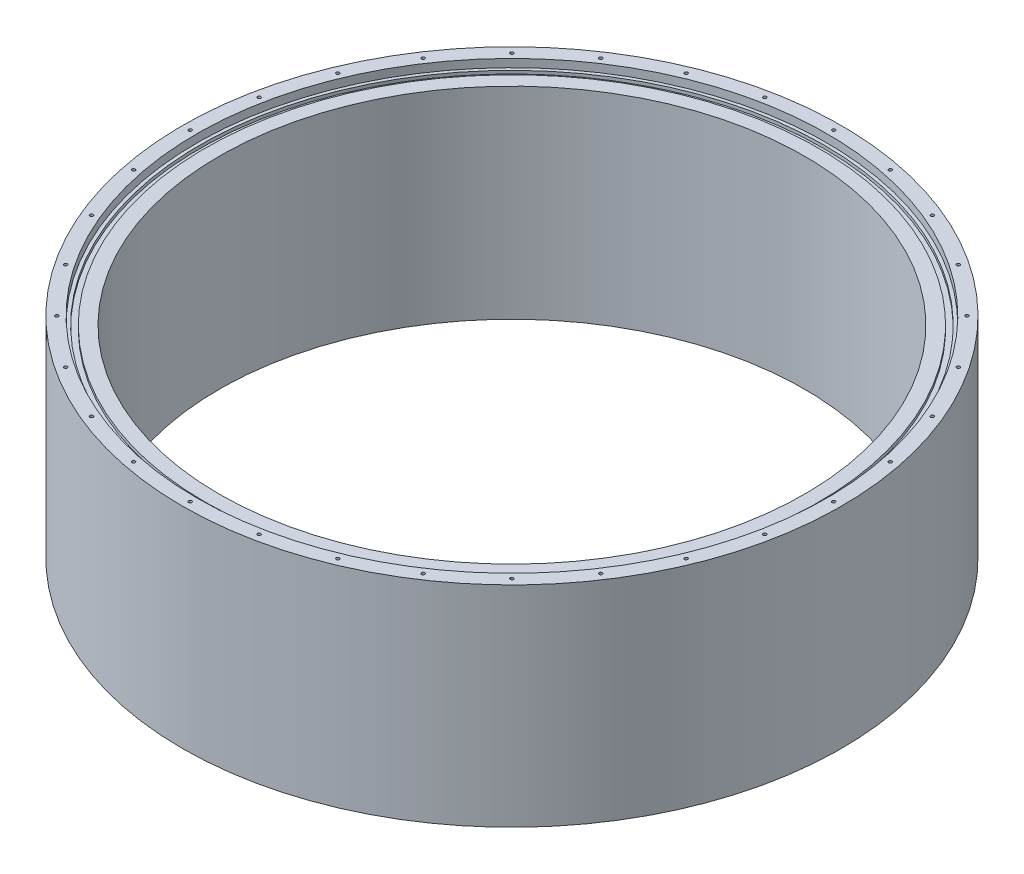
SolidWorks part; units mm, degrees
material "PVC Rigid"
ref_plane "Front" through (0, 0, 0) normal (0, 0, 1) x (1, 0, 0)
ref_plane "Top" through (0, 0, 0) normal (0, 1, 0) x (1, 0, 0)
ref_plane "Right" through (0, 0, 0) normal (1, 0, 0) x (0, 0, -1)
sketch "Sketch1" plane through (0, 0, 0) normal (0, 0, 1) x (1, 0, 0)
  line L0 (225.6, 74.685) -> (243, 74.685)
  line L1 (243, 74.685) -> (243, 80.885)
  line L2 (243, 80.885) -> (254, 80.885)
  line L3 (254, 80.885) -> (254, -80.885)
  line L4 (254, -80.885) -> (225.6, -80.885)
  line L5 (225.6, -80.885) -> (225.6, 74.685)
  line L6 (0, 80.885) -> (0, -80.885) construction
  line L7 (0, 0) -> (225.6, 0) construction
  dimension "D1" = 508
  dimension "D2" = 11
  dimension "D3" = 28.4
  dimension "D4" = 6.2
  dimension "D5" = 161.77
  dimension "D6" = 225.6
  dimension "D7" = 155.57
revolve "Revolve1" add sketch "Sketch1" angle 360 about L6
sketch "Sketch2" plane through (0, 0, 0) normal (0, 0, 1) x (1, 0, 0)
  line L0 (0, 80.885) -> (0, -80.885) construction
  line L1 (254, 80.885) -> (-254, 80.885) construction
  line L2 (-254, -80.885) -> (254, -80.885) construction
  line L3 (240.5, 72.272) -> (240.5, -77.587) construction
  line L4 (236.3344, 74.685) -> (240.5, 74.685)
  line L5 (236.3344, 74.685) -> (236.3344, 72.272)
  line L6 (236.3344, 72.272) -> (240.5, 72.272)
  line L7 (240.5, 74.685) -> (240.5, 72.272)
  line L8 (225.6, 74.685) -> (-225.6, 74.685) construction
  line L9 (225.6, 74.685) -> (-225.6, 74.685) construction
  line L10 (254, -80.885) -> (254, 80.885) construction
  line L12 (236.3344, -78.472) -> (240.5, -78.472) construction
  line L13 (236.3344, -78.472) -> (236.3344, -80.885) construction
  line L14 (236.3344, -80.885) -> (240.5, -80.885) construction
  line L15 (240.5, -78.472) -> (240.5, -80.885) construction
  dimension "D1" = 13.5
  dimension "D2" = 2.413
  dimension "D3" = 4.1656
revolve "Cut-Revolve1" cut sketch "Sketch2" angle 360 about L0
hole_wizard "M3x0.5 Tapped Hole1" positions "Sketch3" profile "Sketch4" tap size "M3x0.5" standard "ANSI Metric"
sketch "Sketch3" plane through (0, 80.885, 0) normal (0, 1, 0) x (1, 0, 0)
  point P0 (248, 0)
  dimension "D1" = 248
sketch "Sketch4" plane through (248, 80.885, 0) normal (1, 0, 0) x (0, 0, 1)
  line L0 (0, 0) -> (0, 10.2511)
  line L1 (0, 10.2511) -> (1.25, 9.5)
  line L2 (1.25, 9.5) -> (1.25, 0)
  line L5 (1.25, 0) -> (0, 0)
  line L10 (0, 10.2511) -> (-1.25, 9.5) construction
  line L11 (0, -6.35) -> (0, 107.95) construction
  dimension "Tap Drill Dia." = 2.5
  dimension "Tap Drill Depth" = 9.5
  dimension "Drill Angle" = 118
cosmetic thread "Hole Thread1" parameters "D1"=8, "D2"=3
pattern_circular "CirPattern1" count 32 over 360 about axis through (0, 0, 0) along (0, 1, 0) of "M3x0.5 Tapped Hole1"
mirror "Mirror1" about plane through (0, 0, 0) normal (0, 1, 0) of "CirPattern1", "M3x0.5 Tapped Hole1"
hole_wizard "Ø5.0mm Dowel Hole1" positions "Sketch5" profile "Sketch6" hole size "Ø5.0" standard "ANSI Metric"
sketch "Sketch5" plane through (0, -80.885, 0) normal (0, -1, 0) x (-1, 0, 0)
  line L2 (0, 0) -> (0, 204.5498) construction
  line L3 (-23.6739, 245.8629) -> (0, 0) construction
  line L4 (0, 0) -> (24.3723, -253.116) construction
  circle A1 centre (0, 0) radius 247
  point P6 (-23.6739, 245.8629)
  point P8 (23.6739, -245.8629)
  dimension "D2" = 494
  dimension "D1" = 5.5
sketch "Sketch6" plane through (-23.6739, -80.885, 245.8629) normal (1, 0, 0) x (0, 0, -1)
  line L0 (0, 0) -> (0, 7.5172)
  line L1 (0, 7.5172) -> (2.525, 6)
  line L2 (2.525, 6) -> (2.525, 0)
  line L5 (2.525, 0) -> (0, 0)
  line L10 (0, 7.5172) -> (-2.525, 6) construction
  line L11 (0, -6.35) -> (0, 107.95) construction
  dimension "Hole Dia." = 5.05
  dimension "Hole Depth" = 6
  dimension "Drill Angle" = 118
